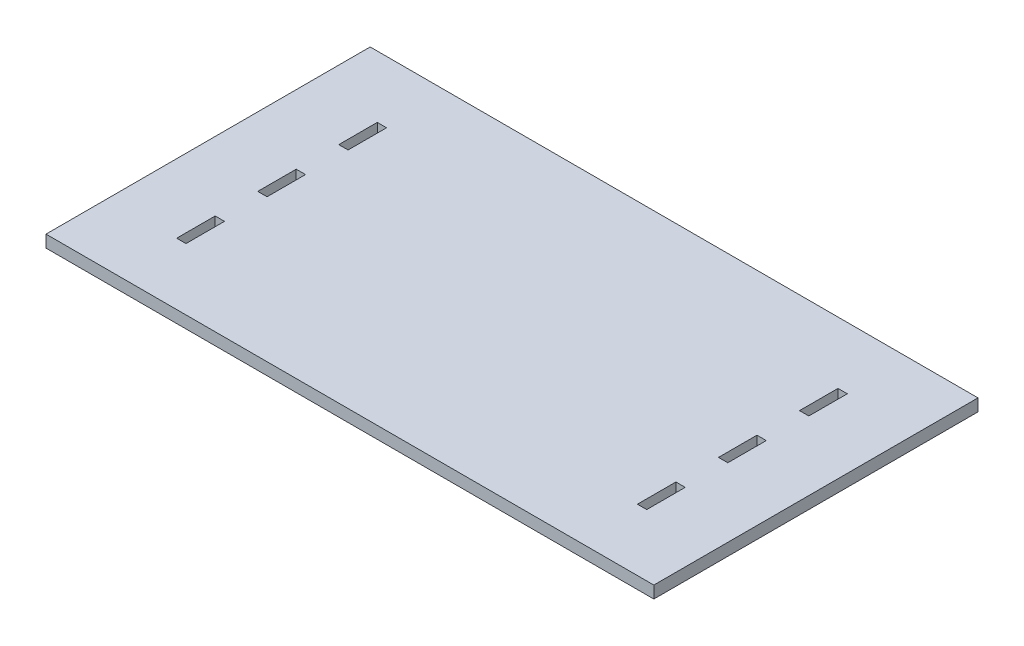
SolidWorks part; units mm, degrees
ref_plane "Alzado" through (0, 0, 0) normal (0, 0, 1) x (1, 0, 0)
ref_plane "Planta" through (0, 0, 0) normal (0, 1, 0) x (1, 0, 0)
ref_plane "Vista lateral" through (0, 0, 0) normal (1, 0, 0) x (0, 0, -1)
sketch "Croquis1" plane through (0, 0, 0) normal (0, 1, 0) x (1, 0, 0)
  line L1 (-75, -40) -> (75, -40)
  line L2 (-75, -40) -> (-75, 40)
  line L3 (-75, 40) -> (75, 40)
  line L4 (75, -40) -> (75, 40)
  line L5 (-75, -40) -> (75, 40) construction
  line L6 (-75, 40) -> (75, -40) construction
  line L7 (55.7, 24.75) -> (58, 24.75)
  line L8 (55.7, 24.75) -> (55.7, 15.25)
  line L9 (55.7, 15.25) -> (58, 15.25)
  line L10 (58, 24.75) -> (58, 15.25)
  line L11 (55.7, 4.75) -> (58, 4.75)
  line L12 (55.7, 4.75) -> (55.7, -4.75)
  line L13 (55.7, -4.75) -> (58, -4.75)
  line L14 (58, 4.75) -> (58, -4.75)
  line L15 (55.7, -15.25) -> (58, -15.25)
  line L16 (55.7, -15.25) -> (55.7, -24.75)
  line L17 (55.7, -24.75) -> (58, -24.75)
  line L18 (58, -15.25) -> (58, -24.75)
  line L19 (-55.7, 15.25) -> (-58, 15.25)
  line L20 (-58, 24.75) -> (-58, 15.25)
  line L21 (-55.7, 24.75) -> (-58, 24.75)
  line L22 (-55.7, 24.75) -> (-55.7, 15.25)
  line L23 (-55.7, -24.75) -> (-58, -24.75)
  line L24 (-58, -15.25) -> (-58, -24.75)
  line L25 (-55.7, -15.25) -> (-58, -15.25)
  line L26 (-55.7, -15.25) -> (-55.7, -24.75)
  line L27 (-55.7, -4.75) -> (-58, -4.75)
  line L28 (-58, 4.75) -> (-58, -4.75)
  line L29 (-55.7, 4.75) -> (-58, 4.75)
  line L30 (-55.7, 4.75) -> (-55.7, -4.75)
  point P0 (0, 0)
  point P10 (58, 20)
  point P15 (55.7, 0)
  point P16 (55.7, 20)
  point P21 (55.7, -20)
  dimension "D1" = 150
  dimension "D2" = 80
  dimension "D3" = 2.3
  dimension "D4" = 9.5
  dimension "D5" = 20
  dimension "D6" = 2.3
  dimension "D7" = 9.5
  dimension "D8" = 20
  dimension "D9" = 2.3
  dimension "D10" = 9.5
  dimension "D11" = 20
  dimension "D12" = 116
  dimension "D13" = 9.5
  dimension "D14" = 9.5
  dimension "D15" = 9.5
  dimension "D16" = 2.3
  dimension "D17" = 2.3
  dimension "D18" = 2.3
  dimension "D19" = 0
  dimension "D20" = 0
  dimension "D21" = 17
  dimension "D22" = 180
  dimension "D23" = 180
extrude "Saliente-Extruir1" add sketch "Croquis1" along normal blind 3
